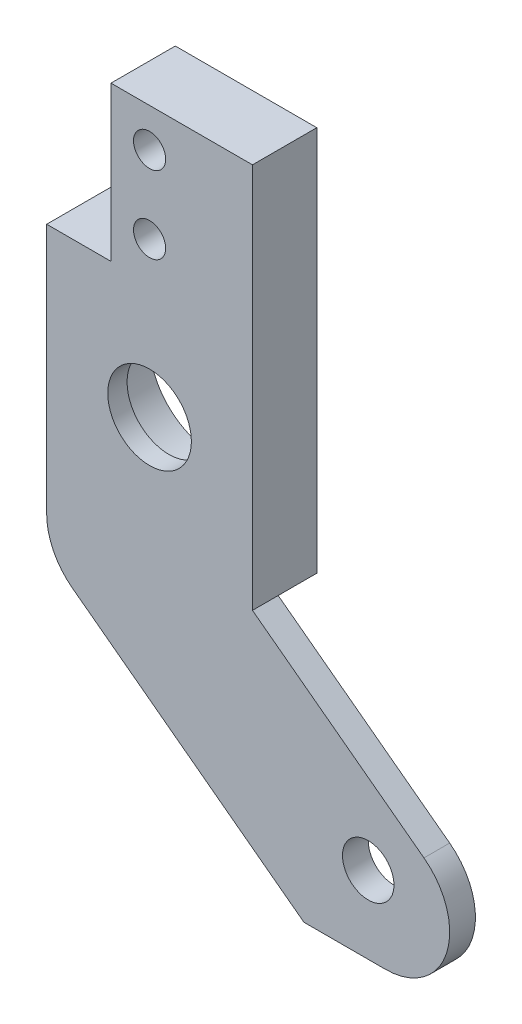
SolidWorks part; units mm, degrees
ref_plane "Front" through (0, 0, 0) normal (0, 0, 1) x (1, 0, 0)
ref_plane "Top" through (0, 0, 0) normal (0, 1, 0) x (1, 0, 0)
ref_plane "Right" through (0, 0, 0) normal (1, 0, 0) x (0, 0, -1)
sketch "Sketch1" plane through (0, 0, 0) normal (0, 0, 1) x (1, 0, 0)
  line L0 (-8, -13) -> (12, -28)
  line L1 (12, -28) -> (33.3333, -28)
  line L2 (33.3333, -28) -> (8, -9)
  line L4 (-8, -13) -> (-8, 21)
  line L5 (-8, 21) -> (8, 21)
  line L6 (8, 21) -> (8, -9)
  dimension "D1" = 34
  dimension "D2" = 8
  dimension "D3" = 30
  dimension "D5" = 15
  dimension "D7" = 21
  dimension "D4" = 16
  dimension "D6" = 20
extrude "Extrude1" add sketch "Sketch1" along normal blind 5
sketch "Sketch3" plane through (0, 0, 0) normal (0, 0, -1) x (-1, 0, 0)
  circle A0 centre (0, 0) radius 5
  dimension "D1" = 10
extrude "Extrude3" cut sketch "Sketch3" against normal blind 3.5
sketch "Sketch4" plane through (0, 0, 3.5) normal (0, 0, -1) x (-1, 0, 0)
  circle A0 centre (0, 0) radius 3.25
  dimension "D1" = 6.5
extrude "Extrude4" cut sketch "Sketch4" against normal up to surface (1.5 mm away) up to face at (7.5556, -6, 5)
sketch "Sketch5" plane through (0, 0, 5) normal (0, 0, 1) x (1, 0, 0)
  line L1 (-8, 21) -> (-3, 21)
  line L2 (-8, 21) -> (-8, 9)
  line L3 (-8, 9) -> (-3, 9)
  line L4 (-3, 21) -> (-3, 9)
  dimension "D1" = 5
  dimension "D2" = 12
extrude "Extrude5" cut sketch "Sketch5" against normal up to surface (5 mm away) up to face at (-5, 0, 0)
sketch "Sketch6" plane through (0, 0, 0) normal (0, 0, -1) x (-1, 0, 0)
  line L0 (-8, -9) -> (-8, 21) construction
  line L1 (-8, 21) -> (3, 21) construction
  circle A0 centre (0, 18) radius 1.25
  circle A1 centre (0, 12) radius 1.25
  dimension "D1" = 2.5
  dimension "D2" = 2.5
  dimension "D3" = 8
  dimension "D4" = 8
  dimension "D5" = 3
  dimension "D6" = 6
extrude "Extrude6" cut sketch "Sketch6" against normal up to surface (5 mm away) up to face at (4.9167, -2.25, 5)
cosmetic thread "Hole Thread1" parameters "D1"=5, "D2"=3
cosmetic thread "Hole Thread2" parameters "D1"=5, "D2"=3
fillet "Fillet1" radius 5 2 edges at (33.3333, -28, 2.5) (-8, -13, 2.5)
sketch "Sketch7" plane through (0, 0, 0) normal (0, 0, -1) x (-1, 0, 0)
  line L0 (-8, -9) -> (8, -9)
  line L1 (8, 9) -> (8, -10.5) construction
  line L2 (8, -9) -> (8, -10.5)
  line L3 (6, -14.5) -> (-12, -28)
  line L4 (-12, -28) -> (-18.3333, -28)
  line L5 (-21.3333, -19) -> (-8, -9)
  arc A0 (8, -10.5) -> (6, -14.5) centre (3, -10.5) cw
  arc A1 (-18.3333, -28) -> (-21.3333, -19) centre (-18.3333, -23) cw
extrude "Extrude7" cut sketch "Sketch7" against normal blind 3
sketch "Sketch8" plane through (0, 0, 3) normal (0, 0, -1) x (-1, 0, 0)
  line L0 (-18.3333, -28) -> (-12, -28) construction
  line L1 (-8, -9) -> (-21.3333, -19) construction
  circle A0 centre (-17, -22) radius 2
  dimension "D1" = 4
  dimension "D3" = 5
  dimension "D2" = 6
extrude "Extrude8" cut sketch "Sketch8" against normal up to surface (2 mm away) up to face at (1.25, 12, 5)
hole_wizard "M3 Tapped Hole1" positions "3DSketch1" profile "Sketch9" tap size "M3" standard "DIN"
sketch3d "3DSketch1"
  line L0 (0, 18, 5) -> (0, 18, 0) construction
  line L1 (0, 12, 5) -> (0, 12, 0) construction
  point P1 (0, 18, 0)
  point P5 (0, 12, 0)
sketch "Sketch9" plane through (0, 18, 0) normal (1, 0, 0) x (0, 1, 0)
  line L0 (0, 0) -> (0, 8.7511)
  line L1 (0, 8.7511) -> (1.25, 8)
  line L2 (1.25, 8) -> (1.25, 0)
  line L5 (1.25, 0) -> (0, 0)
  line L10 (0, 8.7511) -> (-1.25, 8) construction
  line L11 (0, -6.35) -> (0, 107.95) construction
  dimension "Tap Drill Dia." = 2.5
  dimension "Tap Drill Depth" = 8
  dimension "Drill Angle" = 118
